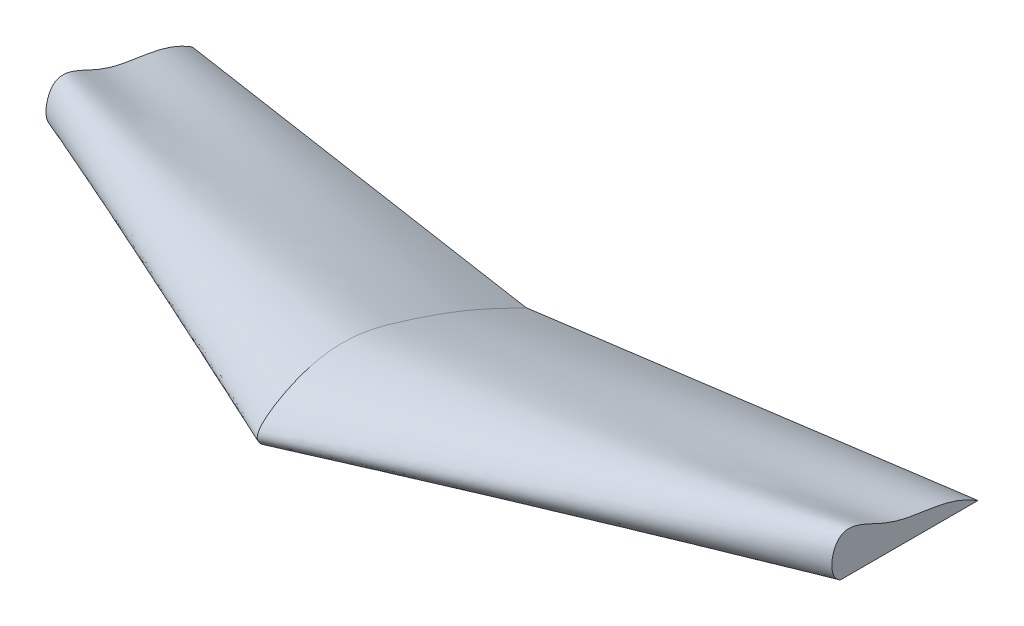
SolidWorks part; units mm, degrees
ref_plane "Front Plane" through (0, 0, 0) normal (0, 0, 1) x (1, 0, 0)
ref_plane "Top Plane" through (0, 0, 0) normal (0, 1, 0) x (1, 0, 0)
ref_plane "Right Plane" through (0, 0, 0) normal (1, 0, 0) x (0, 0, -1)
sketch "Sketch1" plane through (0, 0, 0) normal (1, 0, 0) x (0, 0, -1)
  line L0 (0, 0) -> (152.4, 0)
  spline S0 degree 3 poles (0, 0) (-10.3908, 4.0931) (-32.3981, 12.762) (20.0544, 47.7627) (63.2364, 35.7975) (113.7089, 18.7176) (138.4311, 6.7577) (152.4, 0) knots 0 0 0 0 0.119462 0.253014 0.611882 0.7807 1 1 1 1
  dimension "D1" = 152.4
ref_plane "Plane1" through (254, 0, 0) normal (1, 0, 0) x (0, 0, -1)
sketch "Sketch2" plane through (254, 0, 0) normal (1, 0, 0) x (0, 0, -1)
  line L0 (101.6, 73.4879) -> (101.6, -37.193) construction
  line L1 (101.6, 0) -> (190.5, 0)
  line L2 (0, 0) -> (152.4, 0) construction
  spline S0 degree 3 poles (101.6, 0) (92.9953, 4.421) (97.7728, 35.9802) (144.0289, 6.1061) (167.9585, 14.2278) (190.5, 0) knots 0 0 0 0 0.224188 0.458235 1 1 1 1
  point P8 (0, 0)
  point P9 (0, 0)
  point P10 (0, 0)
  point P12 (0, 0)
  dimension "D1" = 101.6
  dimension "D2" = 88.9
loft "Loft2" add profiles "Sketch1", "Sketch2"
mirror "Mirror18" about plane through (0, 37.4558, -53.7466) normal (1, 0, 0) of "Loft2"
